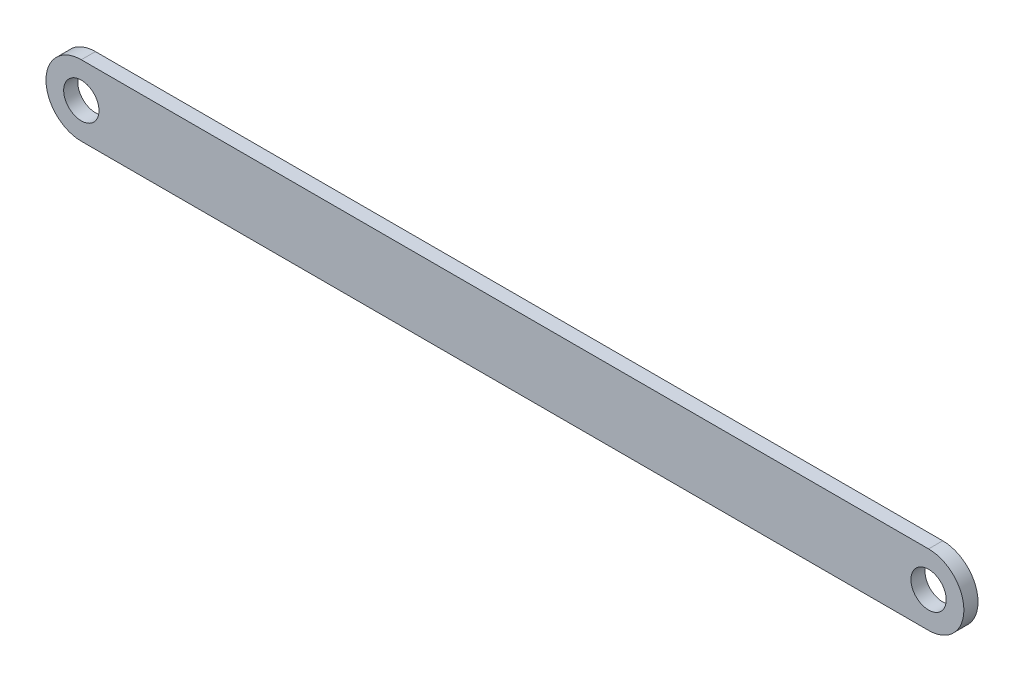
SolidWorks part; units mm, degrees
ref_plane "Front Plane" through (0, 0, 0) normal (0, 0, 1) x (1, 0, 0)
ref_plane "Top Plane" through (0, 0, 0) normal (0, 1, 0) x (1, 0, 0)
ref_plane "Right Plane" through (0, 0, 0) normal (1, 0, 0) x (0, 0, -1)
sketch "Sketch1" plane through (0, 0, 0) normal (0, 0, 1) x (1, 0, 0)
  line L0 (-76.2121, 5.7576) -> (43.7879, 5.7576) construction
  line L1 (-76.2121, 10.7576) -> (43.7879, 10.7576)
  line L2 (-76.2121, 0.7576) -> (43.7879, 0.7576)
  arc A0 (-76.2121, 10.7576) -> (-76.2121, 0.7576) centre (-76.2121, 5.7576) ccw
  arc A1 (43.7879, 0.7576) -> (43.7879, 10.7576) centre (43.7879, 5.7576) ccw
  circle A2 centre (-76.2121, 5.7576) radius 2.5
  circle A3 centre (43.7879, 5.7576) radius 2.5
  point P2 (-16.2121, 5.7576)
  dimension "D1" = 120
  dimension "D2" = 10
extrude "Boss-Extrude1" add sketch "Sketch1" along normal blind 2
